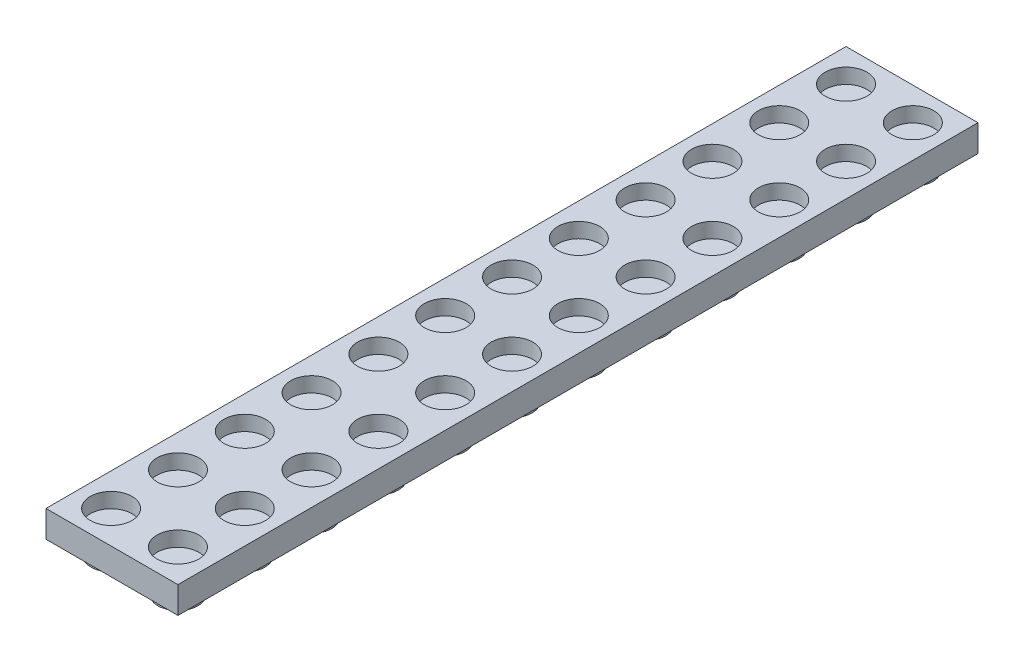
SolidWorks part; units mm, degrees
ref_plane "Спереди" through (0, 0, 0) normal (0, 0, 1) x (1, 0, 0)
ref_plane "Сверху" through (0, 0, 0) normal (0, 1, 0) x (1, 0, 0)
ref_plane "Справа" through (0, 0, 0) normal (1, 0, 0) x (0, 0, -1)
sketch "Эскиз1" plane through (0, 0, 0) normal (0, 1, 0) x (1, 0, 0)
  line L1 (-7.9, 47.9) -> (7.9, 47.9)
  line L2 (-7.9, 47.9) -> (-7.9, -47.9)
  line L3 (-7.9, -47.9) -> (7.9, -47.9)
  line L4 (7.9, 47.9) -> (7.9, -47.9)
  line L5 (-7.9, 47.9) -> (7.9, -47.9) construction
  line L6 (-7.9, -47.9) -> (7.9, 47.9) construction
  point P0 (0, 0)
  dimension "D1" = 95.8
  dimension "D2" = 15.8
extrude "Бобышка-Вытянуть1" add sketch "Эскиз1" along normal blind 3.2
sketch "Эскиз2" plane through (0, 0, 0) normal (0, -1, 0) x (1, 0, 0)
  line L0 (7.9, -47.9) -> (-7.9, -47.9) construction
  line L1 (-7.9, -47.9) -> (-7.9, 47.9) construction
  circle A0 centre (-4, -44) radius 2.4
  circle A1 centre (4, -44) radius 2.4
  circle A2 centre (4, -36) radius 2.4
  circle A3 centre (4, -28) radius 2.4
  circle A4 centre (4, -20) radius 2.4
  circle A5 centre (4, -12) radius 2.4
  circle A6 centre (4, -4) radius 2.4
  circle A7 centre (4, 4) radius 2.4
  circle A8 centre (4, 12) radius 2.4
  circle A9 centre (4, 20) radius 2.4
  circle A10 centre (4, 28) radius 2.4
  circle A11 centre (4, 36) radius 2.4
  circle A12 centre (4, 44) radius 2.4
  circle A13 centre (-4, -36) radius 2.4
  circle A14 centre (-4, -28) radius 2.4
  circle A15 centre (-4, -20) radius 2.4
  circle A16 centre (-4, -12) radius 2.4
  circle A17 centre (-4, -4) radius 2.4
  circle A18 centre (-4, 4) radius 2.4
  circle A19 centre (-4, 12) radius 2.4
  circle A20 centre (-4, 20) radius 2.4
  circle A21 centre (-4, 28) radius 2.4
  circle A22 centre (-4, 36) radius 2.4
  circle A23 centre (-4, 44) radius 2.4
  dimension "D1" = 3.9
  dimension "D2" = 3.9
  dimension "D3" = 2
  dimension "D4" = 12
extrude "Бобышка-Вытянуть3" add sketch "Эскиз2" along normal blind 1.7
sketch "Эскиз3" plane through (0, 3.2, 0) normal (0, 1, 0) x (1, 0, 0)
  line L0 (-7.9, 47.9) -> (-7.9, -47.9) construction
  line L1 (-7.9, -47.9) -> (7.9, -47.9) construction
  circle A0 centre (-4, -44) radius 2.5
  circle A1 centre (4, -44) radius 2.5
  circle A2 centre (4, -36) radius 2.5
  circle A3 centre (4, -28) radius 2.5
  circle A4 centre (4, -20) radius 2.5
  circle A5 centre (4, -12) radius 2.5
  circle A6 centre (4, -4) radius 2.5
  circle A7 centre (4, 4) radius 2.5
  circle A8 centre (4, 12) radius 2.5
  circle A9 centre (4, 20) radius 2.5
  circle A10 centre (4, 28) radius 2.5
  circle A11 centre (4, 36) radius 2.5
  circle A12 centre (4, 44) radius 2.5
  circle A13 centre (-4, -36) radius 2.5
  circle A14 centre (-4, -28) radius 2.5
  circle A15 centre (-4, -20) radius 2.5
  circle A16 centre (-4, -12) radius 2.5
  circle A17 centre (-4, -4) radius 2.5
  circle A18 centre (-4, 4) radius 2.5
  circle A19 centre (-4, 12) radius 2.5
  circle A20 centre (-4, 20) radius 2.5
  circle A21 centre (-4, 28) radius 2.5
  circle A22 centre (-4, 36) radius 2.5
  circle A23 centre (-4, 44) radius 2.5
  dimension "D1" = 3.9
  dimension "D2" = 3.9
  dimension "D3" = 2
  dimension "D4" = 12
extrude "Вырез-Вытянуть1" cut sketch "Эскиз3" against normal blind 1.8
